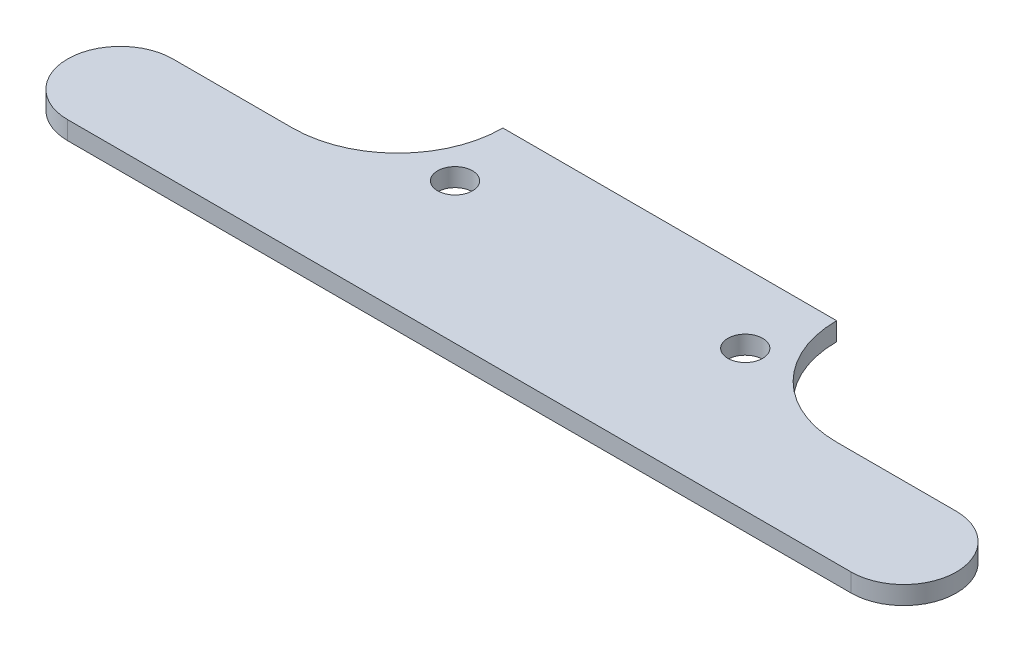
SolidWorks part; units mm, degrees
ref_plane "Front Plane" through (0, 0, 0) normal (0, 0, 1) x (1, 0, 0)
ref_plane "Top Plane" through (0, 0, 0) normal (0, 1, 0) x (1, 0, 0)
ref_plane "Right Plane" through (0, 0, 0) normal (1, 0, 0) x (0, 0, -1)
sketch "Sketch1" plane through (0, 0, 0) normal (0, 1, 0) x (1, 0, 0)
  line L0 (-34.29, 0) -> (34.29, 0) construction
  line L1 (-34.29, 4.6037) -> (34.29, 4.6038)
  line L2 (-34.29, -4.6037) -> (34.29, -4.6037)
  line L3 (-14.605, 13.8112) -> (14.605, 13.8112)
  line L4 (0, -55) -> (0, 55) construction
  arc A0 (-34.29, 4.6037) -> (-34.29, -4.6037) centre (-34.29, 0) ccw
  arc A1 (34.29, -4.6037) -> (34.29, 4.6038) centre (34.29, 0) ccw
  arc A2 (-23.8125, 4.6037) -> (-14.605, 13.8112) centre (-23.8125, 13.8112) ccw
  arc A3 (14.605, 13.8112) -> (23.8125, 4.6037) centre (23.8125, 13.8112) ccw
  circle A4 centre (-12.7, 7.7152) radius 1.524
  circle A5 centre (12.7, 7.7152) radius 1.524
  point P2 (0, 0)
  point P13 (0, 0)
  point P14 (0, 13.8112)
  dimension "D4" = 9.2075
  dimension "D8" = 3.048
  dimension "D1" = 9.2075
  dimension "D2" = 68.58
  dimension "D3" = 18.415
  dimension "D5" = 29.21
  dimension "D6" = 25.4
  dimension "D7" = 6.096
extrude "Boss-Extrude1" add sketch "Sketch1" along normal blind 1.6
